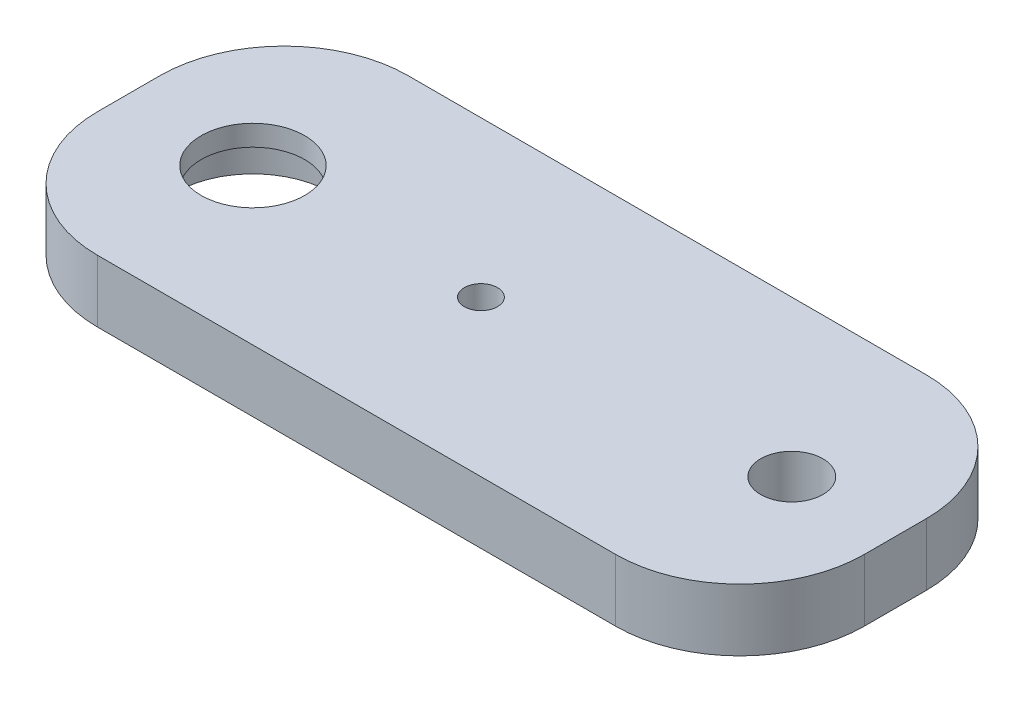
SolidWorks part; units mm, degrees
ref_plane "Front Plane" through (0, 0, 0) normal (0, 0, 1) x (1, 0, 0)
ref_plane "Top Plane" through (0, 0, 0) normal (0, 1, 0) x (1, 0, 0)
ref_plane "Right Plane" through (0, 0, 0) normal (1, 0, 0) x (0, 0, -1)
sketch "Sketch1" plane through (0, 0, 0) normal (0, 1, 0) x (1, 0, 0)
  line L1 (-15, 7.5) -> (15, 7.5)
  line L2 (-15, 7.5) -> (-15, -7.5)
  line L3 (-15, -7.5) -> (15, -7.5)
  line L4 (15, 7.5) -> (15, -7.5)
  line L5 (-15, 7.5) -> (15, -7.5) construction
  line L6 (-15, -7.5) -> (15, 7.5) construction
  point P0 (0, 0)
  dimension "D1" = 30
  dimension "D2" = 15
extrude "Boss-Extrude2" add sketch "Sketch1" along normal blind 3
sketch "Sketch3" plane through (0, 3, 0) normal (0, 1, 0) x (1, 0, 0)
  line L0 (-15, 7.5) -> (-15, -7.5) construction
  circle A0 centre (-9, 0) radius 2.5
  dimension "D2" = 5
  dimension "D1" = 6
extrude "Cut-Extrude1" cut sketch "Sketch3" against normal up to next
fillet "Fillet1" radius 6 2 edges at (-15, 1.5, 7.5) (-15, 1.5, -7.5)
sketch "Sketch5" plane through (0, 0, 7.5) normal (0, 0, 1) x (1, 0, 0)
  line L1 (15, 0) -> (3, 0)
  line L2 (15, 0) -> (15, 3)
  line L3 (15, 3) -> (3, 3)
  line L4 (3, 0) -> (3, 3)
  line L5 (15, 0) -> (3, 3) construction
  line L6 (15, 3) -> (3, 0) construction
  line L7 (-9, 0) -> (15, 0) construction
  line L8 (-9, 3) -> (15, 3) construction
  line L9 (15, 3) -> (15, 0) construction
  point P0 (9, 1.5)
  dimension "D1" = 18
extrude "Boss-Extrude3" add sketch "Sketch5" along normal blind 10
sketch "Sketch6" plane through (0, 0, 0) normal (0, -1, 0) x (-1, 0, 0)
  circle A0 centre (9, 0) radius 3.75
  circle A1 centre (9, 0) radius 2.5 construction
  dimension "D1" = 7.5
extrude "Cut-Extrude4" cut sketch "Sketch6" against normal blind 2
sketch "Sketch7" plane through (0, 0, 0) normal (0, -1, 0) x (-1, 0, 0)
  line L1 (9, 3.75) -> (-11, 3.75)
  line L2 (9, 3.75) -> (9, -3.75)
  line L3 (9, -3.75) -> (-11, -3.75)
  line L4 (-11, 3.75) -> (-11, -3.75)
  line L5 (9, 3.75) -> (-11, -3.75) construction
  line L6 (9, -3.75) -> (-11, 3.75) construction
  point P0 (-1, 0)
  dimension "D1" = 20
  dimension "D2" = 7.5
  dimension "D3" = 6
extrude "Cut-Extrude5" cut sketch "Sketch7" against normal blind 1
sketch "Sketch8" plane through (0, 1, 0) normal (0, -1, 0) x (-1, 0, 0)
  circle A0 centre (-2, 0) radius 0.8
  circle A1 centre (9, 0) radius 2.5 construction
  dimension "D1" = 1.6
  dimension "D2" = 11
extrude "Cut-Extrude6" cut sketch "Sketch8" against normal up to next
sketch "Sketch9" plane through (0, 0, 0) normal (0, 1, 0) x (1, 0, 0)
  line L1 (3, -17.5) -> (15, -17.5)
  line L2 (3, -17.5) -> (3, -7.5)
  line L3 (3, -7.5) -> (15, -7.5)
  line L4 (15, -17.5) -> (15, -7.5)
  line L5 (3, -17.5) -> (15, -7.5) construction
  line L6 (3, -7.5) -> (15, -17.5) construction
  point P0 (9, -12.5)
  point P5 (0, 0)
  point P7 (0, 0)
  point P9 (0, 0)
extrude "Cut-Extrude7" cut sketch "Sketch9" along normal up to next
sketch "Sketch10" plane through (15, 0, 0) normal (1, 0, 0) x (0, 0, -1)
  line L1 (-7.5, 3) -> (7.5, 3)
  line L2 (-7.5, 3) -> (-7.5, 0)
  line L3 (-7.5, 0) -> (7.5, 0)
  line L4 (7.5, 3) -> (7.5, 0)
  line L5 (-7.5, 3) -> (7.5, 0) construction
  line L6 (-7.5, 0) -> (7.5, 3) construction
  point P0 (0, 1.5)
  point P6 (0, 0)
  point P8 (0, 0)
extrude "Boss-Extrude4" add sketch "Sketch10" along normal blind 7
sketch "Sketch11" plane through (0, 3, 0) normal (0, 1, 0) x (1, 0, 0)
  line L0 (22, 7.5) -> (22, -7.5) construction
  circle A0 centre (17, 0) radius 1.5
  point P2 (0, 0)
  dimension "D1" = 3
  dimension "D2" = 5
extrude "Cut-Extrude8" cut sketch "Sketch11" against normal up to next
fillet "Fillet2" radius 6 2 edges at (22, 1.5, 7.5) (22, 1.5, -7.5)
